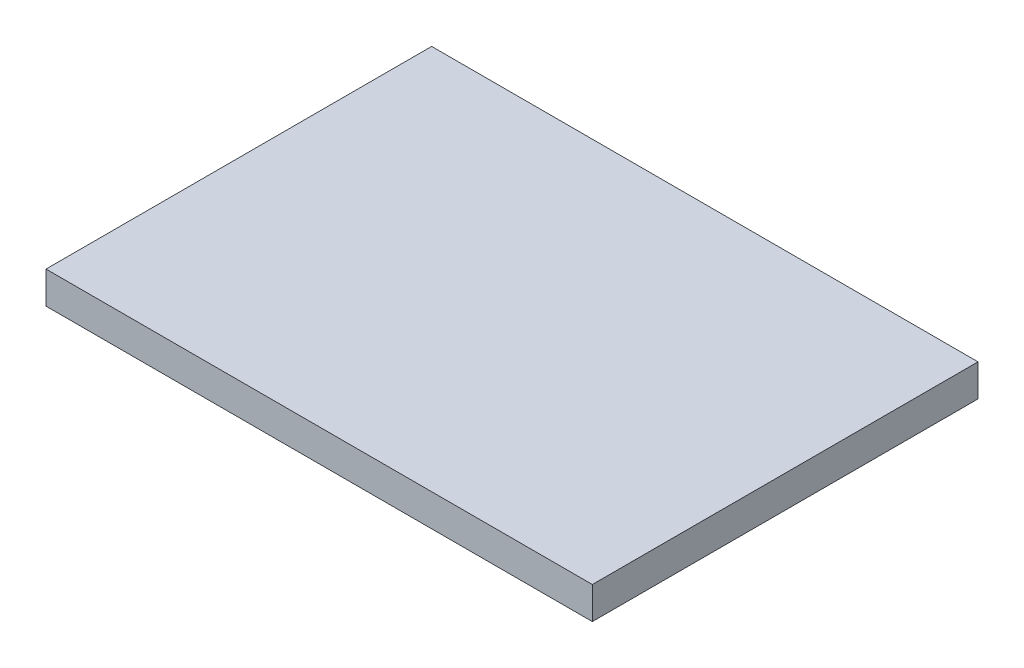
SolidWorks part; units mm, degrees
ref_plane "Front Plane" through (0, 0, 0) normal (0, 0, 1) x (1, 0, 0)
ref_plane "Top Plane" through (0, 0, 0) normal (0, 1, 0) x (1, 0, 0)
ref_plane "Right Plane" through (0, 0, 0) normal (1, 0, 0) x (0, 0, -1)
sketch "Sketch1" plane through (0, 0, 0) normal (0, 1, 0) x (1, 0, 0)
  line L1 (-215.9, -152.4) -> (215.9, -152.4)
  line L2 (-215.9, -152.4) -> (-215.9, 152.4)
  line L3 (-215.9, 152.4) -> (215.9, 152.4)
  line L4 (215.9, -152.4) -> (215.9, 152.4)
  line L5 (-215.9, -152.4) -> (215.9, 152.4) construction
  line L6 (-215.9, 152.4) -> (215.9, -152.4) construction
  point P0 (0, 0)
  dimension "D1" = 431.8
  dimension "D2" = 304.8
extrude "Boss-Extrude1" add sketch "Sketch1" along normal blind 25.4
